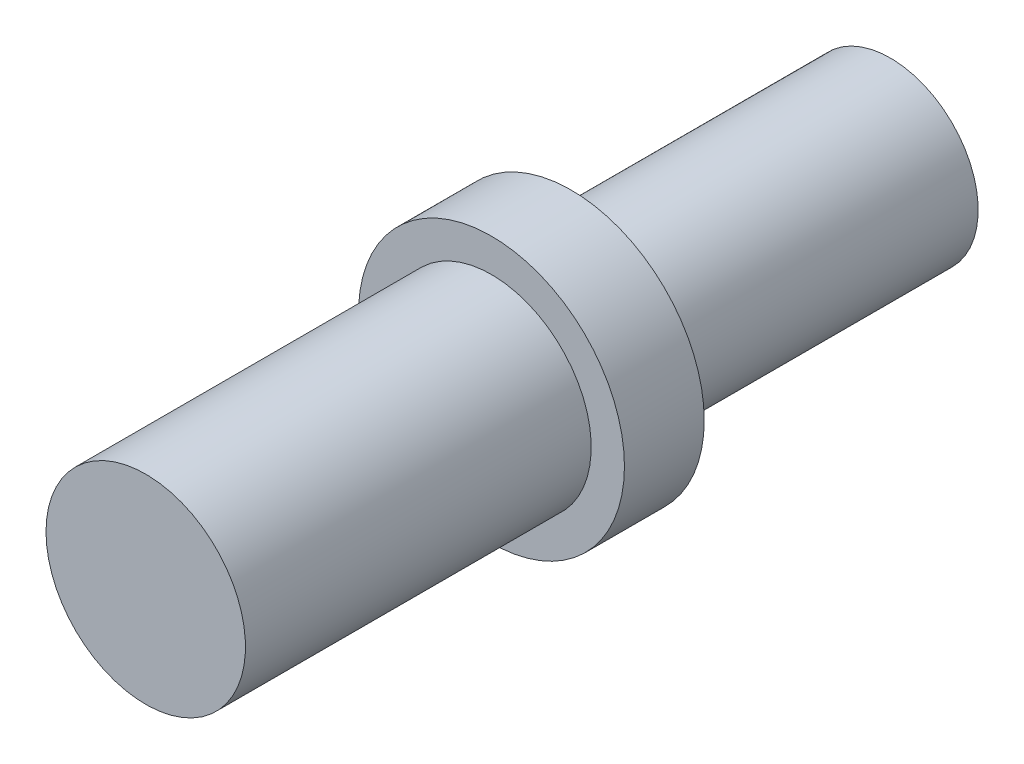
SolidWorks part; units mm, degrees
ref_plane "前基準面" through (0, 0, 0) normal (0, 0, 1) x (1, 0, 0)
ref_plane "上基準面" through (0, 0, 0) normal (0, 1, 0) x (1, 0, 0)
ref_plane "右基準面" through (0, 0, 0) normal (1, 0, 0) x (0, 0, -1)
sketch "草圖1" plane through (0, 0, 0) normal (0, 0, 1) x (1, 0, 0)
  circle A0 centre (-36.5655, -95.3074) radius 5
  circle A1 centre (-36.5655, -95.3074) radius 3.5 construction
  dimension "D1" = 10
  dimension "D2" = 0
extrude "填料-伸長1" add sketch "草圖1" along normal blind 3
sketch "草圖2" plane through (0, 0, 0) normal (0, 0, -1) x (-1, 0, 0)
  circle A2 centre (36.5655, -95.3074) radius 3.3
  circle A3 centre (36.5655, -95.3074) radius 3.3
  dimension "D1" = 1.7
extrude "填料-伸長2" add sketch "草圖2" along normal blind 12
sketch "草圖4" plane through (0, 0, 3) normal (0, 0, 1) x (1, 0, 0)
  circle A2 centre (-36.5655, -95.3074) radius 3.75
  circle A3 centre (-36.5655, -95.3074) radius 3.75
  dimension "D1" = 1.25
extrude "填料-伸長3" add sketch "草圖4" along normal blind 13
